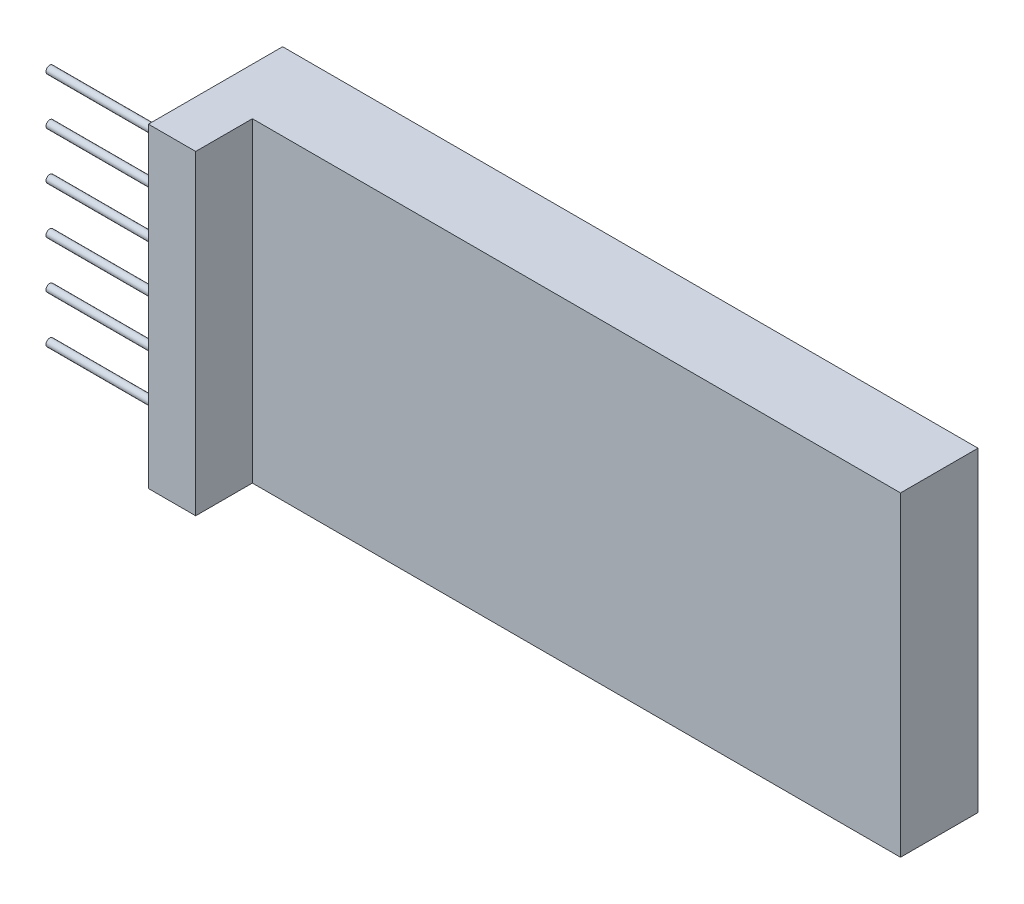
SolidWorks part; units mm, degrees
ref_plane "前视基准面" through (0, 0, 0) normal (0, 0, 1) x (1, 0, 0)
ref_plane "上视基准面" through (0, 0, 0) normal (0, 1, 0) x (1, 0, 0)
ref_plane "右视基准面" through (0, 0, 0) normal (1, 0, 0) x (0, 0, -1)
sketch "草图1" plane through (0, 0, 0) normal (0, 0, 1) x (1, 0, 0)
  line L1 (0, 0) -> (36.8, 0)
  line L2 (0, 0) -> (0, 16.7)
  line L3 (0, 16.7) -> (36.8, 16.7)
  line L4 (36.8, 0) -> (36.8, 16.7)
  dimension "D1" = 36.8
  dimension "D2" = 16.7
extrude "凸台-拉伸1" add sketch "草图1" along normal blind 4.1
sketch "草图2" plane through (0, 0, 4.1) normal (0, 0, 1) x (1, 0, 0)
  line L0 (0, 0) -> (36.8, 0) construction
  line L1 (0, 16.7) -> (2.5, 16.7)
  line L2 (0, 16.7) -> (0, 0)
  line L3 (0, 0) -> (2.5, 0)
  line L4 (2.5, 16.7) -> (2.5, 0)
extrude "凸台-拉伸2" add sketch "草图2" along normal blind 3
sketch "草图3" plane through (0, 0, 0) normal (-1, 0, 0) x (0, 0, 1)
  circle A0 centre (5.6713, 15.1645) radius 0.2
  circle A1 centre (5.6713, 12.6645) radius 0.2
  circle A2 centre (5.6713, 10.1645) radius 0.2
  circle A3 centre (5.6713, 7.6645) radius 0.2
  circle A4 centre (5.6713, 5.1645) radius 0.2
  circle A5 centre (5.6713, 2.6645) radius 0.2
  dimension "D1" = 6
extrude "凸台-拉伸3" add sketch "草图3" along normal blind 6.65
